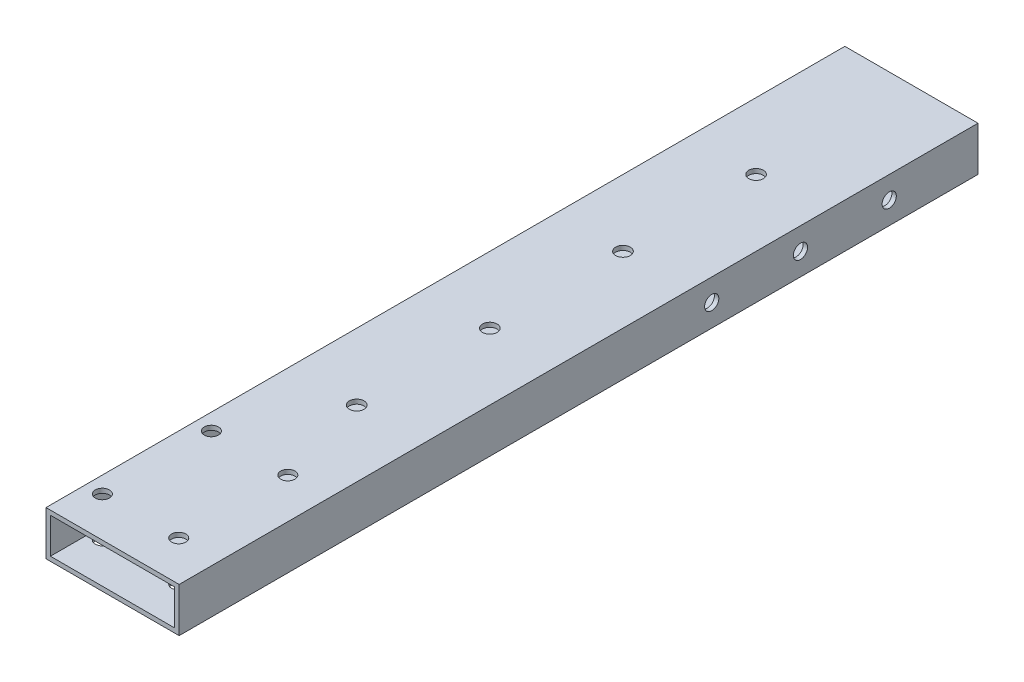
SolidWorks part; units mm, degrees
material "6061 合金"
ref_plane "前视基准面" through (0, 0, 0) normal (0, 0, 1) x (1, 0, 0)
ref_plane "上视基准面" through (0, 0, 0) normal (0, 1, 0) x (1, 0, 0)
ref_plane "右视基准面" through (0, 0, 0) normal (1, 0, 0) x (0, 0, -1)
other "Configuration Table"
sketch "草图1" plane through (0, 0, 0) normal (0, 0, 1) x (1, 0, 0)
  line L1 (-15, 5) -> (15, 5)
  line L2 (-15, 5) -> (-15, -5)
  line L3 (-15, -5) -> (15, -5)
  line L4 (15, 5) -> (15, -5)
  line L5 (-15, 5) -> (15, -5) construction
  line L6 (-15, -5) -> (15, 5) construction
  line L7 (-13, 3) -> (13, 3)
  line L8 (-13, 3) -> (-13, -3)
  line L9 (-13, -3) -> (13, -3)
  line L10 (13, 3) -> (13, -3)
  line L11 (-13, 3) -> (13, -3) construction
  line L12 (-13, -3) -> (13, 3) construction
  point P0 (0, 0)
  point P6 (0, 0)
  dimension "2" = 2
  dimension "D2" = 2
  dimension "D3" = 10
  dimension "D4" = 30
extrude "凸台-拉伸1" add sketch "草图1" along normal blind 330
sketch "草图2" plane through (0, 5, 0) normal (0, 1, 0) x (1, 0, 0)
  line L0 (-15, -330) -> (-15, 0) construction
  line L1 (15, -330) -> (-15, -330) construction
  circle A0 centre (-11.3, -321) radius 1.6
  dimension "D1" = 3.2
  dimension "D2" = 3.7
  dimension "D3" = 9
extrude "切除-拉伸1" cut sketch "草图2" against normal through all
sketch "草图3" plane through (0, 5, 0) normal (0, 1, 0) x (1, 0, 0)
  line L0 (15, -330) -> (15, 0) construction
  line L1 (15, -330) -> (-15, -330) construction
  circle A0 centre (5.9073, -296.4254) radius 1.6
  circle A1 centre (5.9073, -296.4254) radius 2
  circle A2 centre (5.9073, -296.4254) radius 2 construction
  circle A3 centre (-11.3, -321) radius 2
  circle A4 centre (-11.3, -321) radius 2 construction
  circle A113 centre (0, -215) radius 1.65
  circle A115 centre (0, -185) radius 1.65
  circle A121 centre (0, -275) radius 1.65
  circle A123 centre (0, -245) radius 1.65
  dimension "D3" = 3.2
  dimension "D4" = 3.3
  dimension "D5" = 3.3
  dimension "D6" = 3.3
  dimension "D7" = 3.3
  dimension "D8" = 30
  dimension "D9" = 30
  dimension "D10" = 30
  dimension "D11" = 15
  dimension "D12" = 15
  dimension "D13" = 15
  dimension "D14" = 15
  dimension "D15" = 55
  dimension "D1" = 0
  dimension "D2" = 0
extrude "切除-拉伸2" cut sketch "草图3" against normal through all
sketch "草图4" plane through (-15, 0, 0) normal (-1, 0, 0) x (0, 0, 1)
  line L0 (170, 0) -> (190, 0) construction
  circle A0 centre (170, 0) radius 1.6
  circle A1 centre (190, 0) radius 1.6
  circle A2 centre (210, 0) radius 1.6
  dimension "D1" = 170
  dimension "D2" = 3.2
  dimension "D4" = 20
  dimension "D3" = 3
extrude "切除-拉伸3" cut sketch "草图4" against normal through all
sketch "草图5" plane through (0, 5, 0) normal (0, 1, 0) x (1, 0, 0)
  line L0 (0, -105) -> (0, -15) construction
  line L1 (-9, -105) -> (-9, -15)
  line L2 (9, -105) -> (9, -15)
  line L3 (15, -330) -> (15, 0) construction
  line L4 (15, 0) -> (-15, 0) construction
  arc A0 (-9, -105) -> (9, -105) centre (0, -105) ccw
  arc A1 (9, -15) -> (-9, -15) centre (0, -15) ccw
  point P2 (0, -60)
  dimension "D2" = 15
  dimension "D1" = 6
  dimension "D3" = 90
extrude "切除-拉伸4" [suppressed] cut sketch "草图5" against normal through all
sketch "草图6" plane through (0, 0, 0) normal (0, 0, -1) x (-1, 0, 0)
  line L0 (-15, 5) -> (15, 5) construction
  line L1 (-14, 4) -> (14, 4)
  line L2 (-14, 4) -> (-14, -4)
  line L3 (-14, -4) -> (14, -4)
  line L4 (14, 4) -> (14, -4)
  line L5 (15, 5) -> (15, -5) construction
  line L6 (-15, -5) -> (-15, 5) construction
  line L7 (15, -5) -> (-15, -5) construction
  dimension "D1" = 1
  dimension "D2" = 1
  dimension "D3" = 1
  dimension "D4" = 1
extrude "切除-拉伸5" cut sketch "草图6" against normal blind 355
sketch "草图7" plane through (0, 5, 0) normal (0, 1, 0) x (1, 0, 0)
  line L0 (5.9073, -296.4254) -> (5.9073, -334.8727) construction
  line L1 (-11.3, -321) -> (30.9723, -321) construction
  line L2 (-11.3, -321) -> (-11.3, -288.6331) construction
  line L3 (5.9073, -296.4254) -> (-31.0637, -296.4254) construction
  circle A0 centre (5.9073, -321) radius 1.6
  circle A1 centre (-11.3, -296.4254) radius 1.6
  dimension "D1" = 3.2
  dimension "D2" = 3.2
extrude "切除-拉伸6" cut sketch "草图7" against normal blind 14
sketch "草图8" plane through (0, 0, 330) normal (0, 0, 1) x (1, 0, 0)
  line L1 (-15, 5) -> (15, 5)
  line L2 (-15, 5) -> (-15, -5)
  line L3 (-15, -5) -> (15, -5)
  line L4 (15, 5) -> (15, -5)
sketch "草图9" plane through (0, 0, 0) normal (0, 0, -1) x (-1, 0, 0)
  line L1 (-15, 5) -> (15, 5)
  line L2 (-15, 5) -> (-15, -5)
  line L3 (-15, -5) -> (15, -5)
  line L4 (15, 5) -> (15, -5)
extrude "切除-拉伸7" cut sketch "草图9" against normal blind 150
